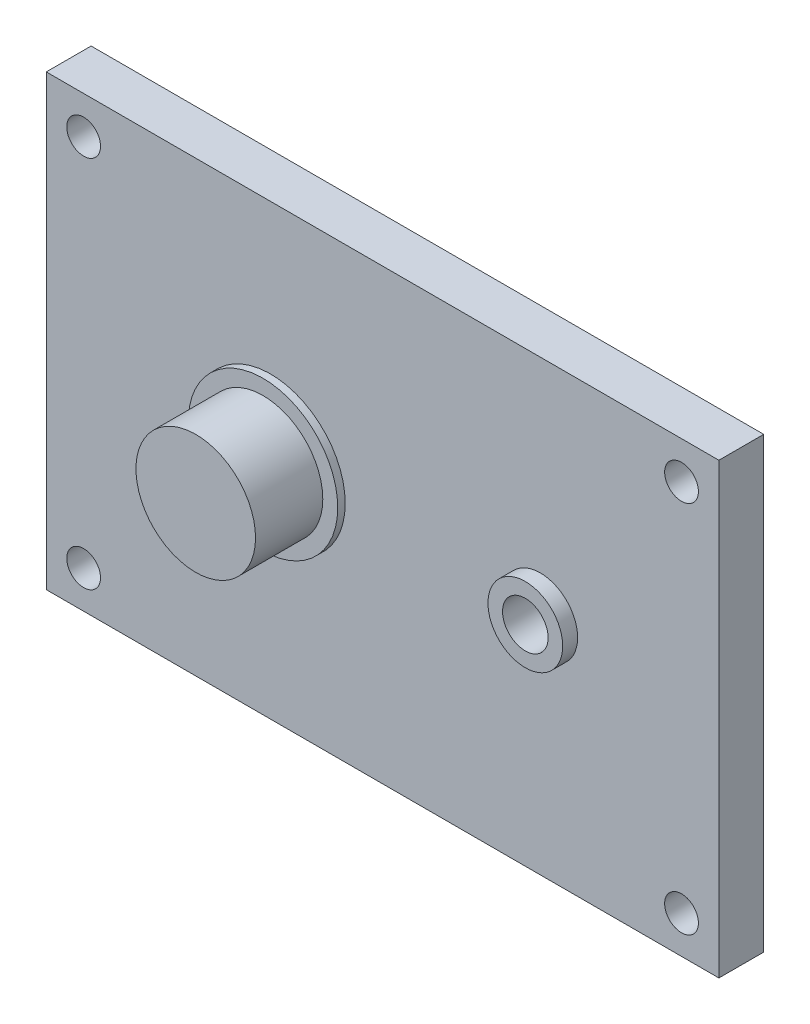
SolidWorks part; units mm, degrees
material "6061-T6 (SS)"
ref_plane "Front Plane" through (0, 0, 0) normal (0, 0, 1) x (1, 0, 0)
ref_plane "Top Plane" through (0, 0, 0) normal (0, 1, 0) x (1, 0, 0)
ref_plane "Right Plane" through (0, 0, 0) normal (1, 0, 0) x (0, 0, -1)
sketch "Sketch1" plane through (0, 0, 0) normal (0, 0, 1) x (1, 0, 0)
  line L0 (0, 0) -> (18.05, 0) construction
  line L1 (18.05, 0) -> (32.6, 0) construction
  line L2 (32.6, 0) -> (42.45, 0) construction
  line L3 (0, 0) -> (-15, 0) construction
  line L4 (-15, 15) -> (30, 15)
  line L5 (-15, 15) -> (-15, -15)
  line L6 (-15, -15) -> (30, -15)
  line L7 (30, 15) -> (30, -15)
  circle A0 centre (0, 0) radius 3.475 construction
  circle A1 centre (18.05, 0) radius 1.525
  circle A2 centre (32.6, 0) radius 1.025 construction
  circle A3 centre (42.45, 0) radius 1.025 construction
  circle A4 centre (42.45, 0) radius 10 construction
  circle A5 centre (0, 0) radius 13.35 construction
  circle A6 centre (18.05, 0) radius 11.9 construction
  dimension "D1" = 6.95
  dimension "D2" = 3.05
  dimension "D4" = 2.05
  dimension "D6" = 2.05
  dimension "D10" = 20
  dimension "D12" = 26.7
  dimension "D13" = 23.8
  dimension "D3" = 18.05
  dimension "D5" = 14.55
  dimension "D7" = 9.85
  dimension "D8" = 30
  dimension "D9" = 15
  dimension "D11" = 45
extrude "Boss-Extrude1" add sketch "Sketch1" along normal blind 3
sketch "Sketch2" plane through (0, 0, 3) normal (0, 0, 1) x (1, 0, 0)
  circle A0 centre (0, 0) radius 4
  dimension "D1" = 8
extrude "Boss-Extrude2" add sketch "Sketch2" along normal blind 5
sketch "Sketch3" plane through (0, 0, 3) normal (0, 0, 1) x (1, 0, 0)
  circle A0 centre (0, 0) radius 4 construction
  circle A1 centre (0, 0) radius 4
  circle A2 centre (0, 0) radius 5
  dimension "D2" = 10
extrude "Boss-Extrude3" add sketch "Sketch3" along normal blind 0.5
hole_wizard "#2 Clearance Hole1" positions "Sketch5" profile "Sketch4" hole size "#2" standard "ANSI Inch" end condition through all
sketch "Sketch5" plane through (0, 0, 3) normal (0, 0, 1) x (1, 0, 0)
  line L0 (-12.5, -12.5) -> (-12.5, 12.5) construction
  line L1 (-12.5, 12.5) -> (27.5, 12.5) construction
  line L3 (27.5, 12.5) -> (27.5, -12.5) construction
  line L7 (-12.5, -12.5) -> (27.5, -12.5) construction
  line L9 (-15, 15) -> (-15, -15) construction
  line L10 (30, 15) -> (-15, 15) construction
  line L11 (-15, -15) -> (30, -15) construction
  line L12 (30, -15) -> (30, 15) construction
  point P0 (-12.5, 12.5)
  point P2 (-12.5, -12.5)
  point P4 (27.5, -12.5)
  point P6 (27.5, 12.5)
  dimension "D1" = 2.5
  dimension "D2" = 2.5
  dimension "D3" = 2.5
  dimension "D4" = 2.5
sketch "Sketch4" plane through (-12.5, 12.5, 3) normal (1, 0, 0) x (0, -1, 0)
  line L0 (0, 0) -> (0, 3)
  line L1 (0, 3) -> (1.1303, 3)
  line L2 (1.1303, 3) -> (1.1303, 0)
  line L5 (1.1303, 0) -> (0, 0)
  line L11 (0, -6.35) -> (0, 107.95) construction
  dimension "Thru Hole Dia." = 2.2606
  dimension "Thru Hole Depth" = 3
sketch "Sketch6" plane through (0, 0, 3) normal (0, 0, 1) x (1, 0, 0)
  circle A0 centre (18.05, 0) radius 2.5
  circle A1 centre (18.05, 0) radius 1.525 construction
  circle A2 centre (18.05, 0) radius 1.525
  dimension "D1" = 5
extrude "Boss-Extrude4" add sketch "Sketch6" along normal blind 1
